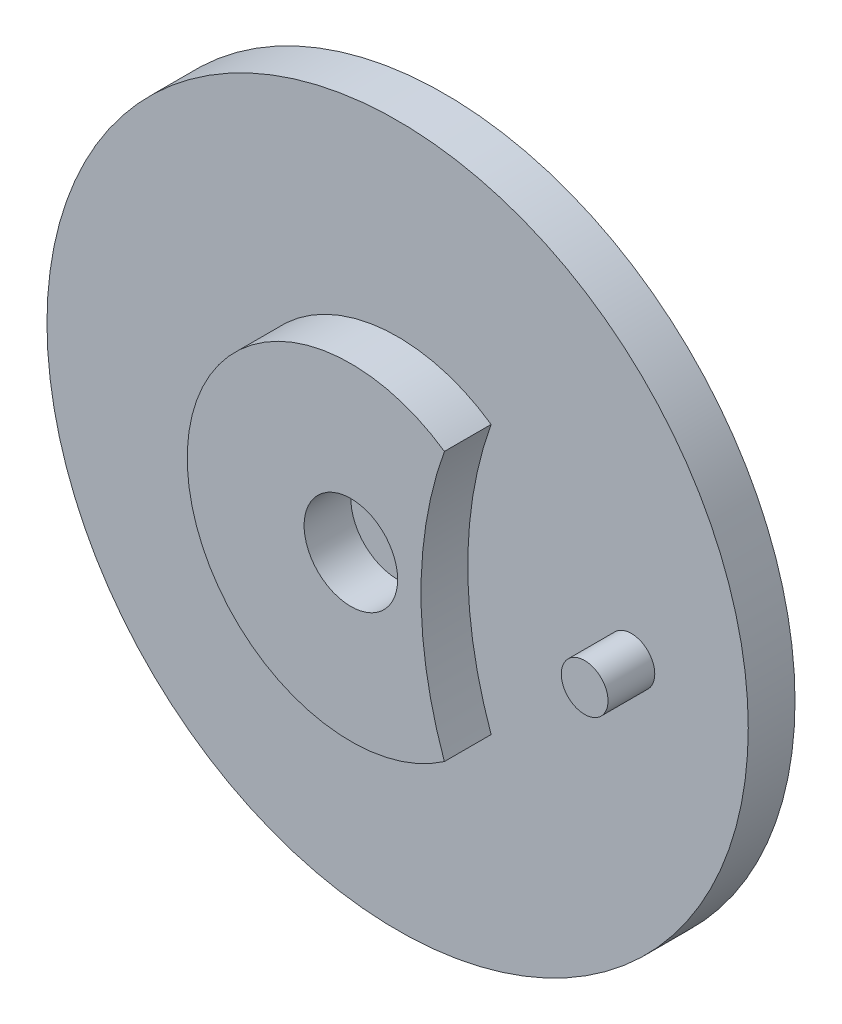
SolidWorks part; units mm, degrees
ref_plane "Alzado" through (0, 0, 0) normal (0, 0, 1) x (1, 0, 0)
ref_plane "Planta" through (0, 0, 0) normal (0, 1, 0) x (1, 0, 0)
ref_plane "Vista lateral" through (0, 0, 0) normal (1, 0, 0) x (0, 0, -1)
sketch "Croquis1" plane through (0, 0, 0) normal (0, 0, 1) x (1, 0, 0)
  circle A0 centre (0, 0) radius 75
  dimension "D1" = 150
extrude "Saliente-Extruir1" add sketch "Croquis1" along normal blind 20
sketch "Croquis2" plane through (0, 0, 20) normal (0, 0, 1) x (1, 0, 0)
  circle A0 centre (0, 0) radius 10
  dimension "D1" = 20
extrude "Cortar-Extruir1" cut sketch "Croquis2" against normal blind 10
sketch "Croquis3" plane through (0, 0, 20) normal (0, 0, 1) x (1, 0, 0)
  circle A0 centre (0, 0) radius 35
  circle A1 centre (0, 0) radius 75
  dimension "D1" = 70
  dimension "D2" = 150
extrude "Cortar-Extruir2" cut sketch "Croquis3" against normal blind 10
sketch "Croquis4" plane through (0, 0, 10) normal (0, 0, 1) x (1, 0, 0)
  line L0 (0, 0) -> (50, 0) construction
  circle A0 centre (50, 0) radius 5
  dimension "D2" = 10
  dimension "D1" = 50
extrude "Saliente-Extruir3" add sketch "Croquis4" along normal blind 10
sketch "Croquis5" plane through (0, 0, 20) normal (0, 0, 1) x (1, 0, 0)
  line L0 (0, 0) -> (100, 0) construction
  arc A0 (20, 28.7228) -> (20, -28.7228) centre (100, 0) ccw
  arc A1 (20, -28.7228) -> (20, 28.7228) centre (0, 0) ccw
  dimension "D2" = 85
  dimension "D3" = 35
  dimension "D1" = 100
extrude "Cortar-Extruir3" cut sketch "Croquis5" against normal blind 10
